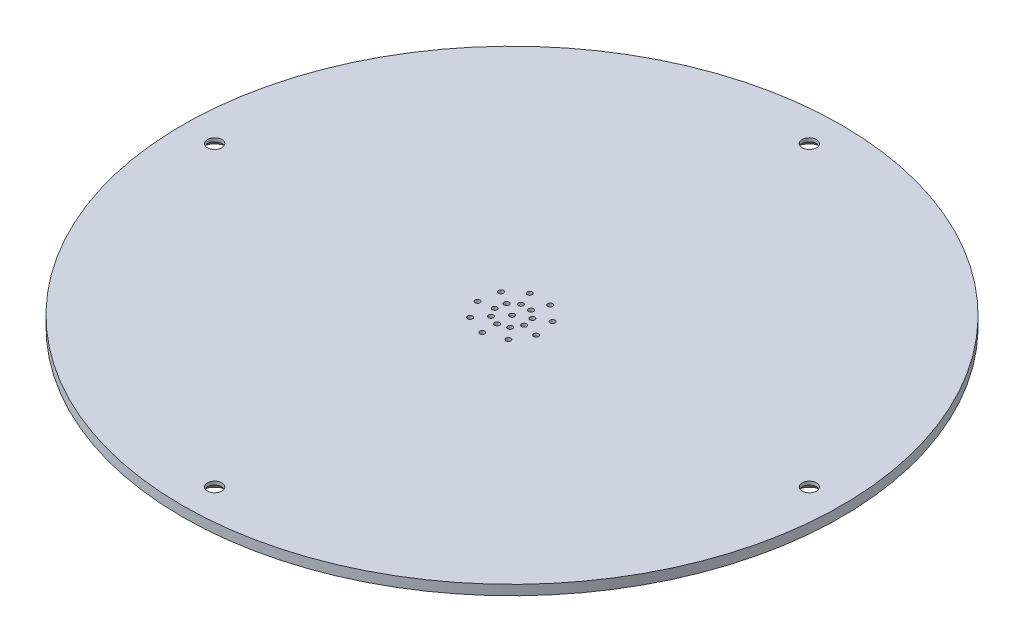
SolidWorks part; units mm, degrees
ref_plane "Front Plane" through (0, 0, 0) normal (0, 0, 1) x (1, 0, 0)
ref_plane "Top Plane" through (0, 0, 0) normal (0, 1, 0) x (1, 0, 0)
ref_plane "Right Plane" through (0, 0, 0) normal (1, 0, 0) x (0, 0, -1)
sketch "Sketch3" plane through (0, 0, 0) normal (0, 1, 0) x (1, 0, 0)
  circle A0 centre (0, 0) radius 66.5
  dimension "D1" = 133
extrude "Boss-Extrude1" add sketch "Sketch3" along normal blind 2
sketch "Sketch4" plane through (0, 0, 0) normal (0, -1, 0) x (-1, 0, 0)
  line L0 (0, 0) -> (60, 0) construction
  line L1 (0, 0) -> (0, -60) construction
  line L2 (0, 0) -> (-60, 0) construction
  line L3 (0, 0) -> (0, 60) construction
  line L4 (0, 0) -> (-38.8909, 38.8909) construction
  circle A0 centre (-38.8909, 38.8909) radius 2.5
  point P9 (0, 0)
  dimension "D5" = 5
  dimension "D1" = 60
  dimension "D3" = 45
  dimension "D4" = 55
  dimension "D2" = 4
hole_wizard "CSK for M2.5 Flat Head Machine Screw2" positions "Sketch7" profile "Sketch8" countersink size "M2.5" standard "ANSI Metric"
sketch "Sketch7" plane through (0, 0, 0) normal (0, -1, 0) x (-1, 0, 0)
  point P0 (-60, 0)
  point P3 (0, 60)
  point P6 (60, 0)
  point P9 (0, -60)
sketch "Sketch8" plane through (60, 0, 0) normal (1, 0, 0) x (0, 0, -1)
  line L0 (0, 0) -> (0, 2.8712)
  line L1 (0, 2.8712) -> (1.45, 2)
  line L2 (1.45, 2) -> (1.45, 1.3)
  line L3 (1.45, 1.3) -> (2.75, 0)
  line L5 (2.75, 0) -> (0, 0)
  line L6 (-1.45, 1.3) -> (-2.75, 0) construction
  line L10 (0, 2.8712) -> (-1.45, 2) construction
  line L11 (0, -6.35) -> (0, 107.95) construction
  dimension "Hole Dia." = 2.9
  dimension "Hole Depth" = 2
  dimension "Near C'Sink Dia." = 5.5
  dimension "Near C'Sink Angle" = 90
  dimension "Drill Angle" = 118
extrude "Cut-Extrude1" cut sketch "Sketch4" against normal blind 1 contours A0
pattern_circular "CirPattern1" count 4 over 360 about axis through (-0.0554, 0, 0.0554) along (0, 1, 0) of "Cut-Extrude1"
sketch "Sketch9" plane through (0, 0, 0) normal (0, -1, 0) x (1, 0, 0)
  line L0 (0, 0) -> (0, 3) construction
  line L1 (0, 3) -> (0, 6) construction
  circle A0 centre (0, 0) radius 0.5
  circle A1 centre (0, 3) radius 0.5
  circle A2 centre (0, 6) radius 0.5
  dimension "D1" = 1
  dimension "D2" = 3
  dimension "D3" = 3
extrude "Cut-Extrude2" cut sketch "Sketch9" against normal through all
pattern_circular "CirPattern2" count 9 over 360 about axis through (0, 0, 0) along (0, 1, 0) of "Cut-Extrude2"
